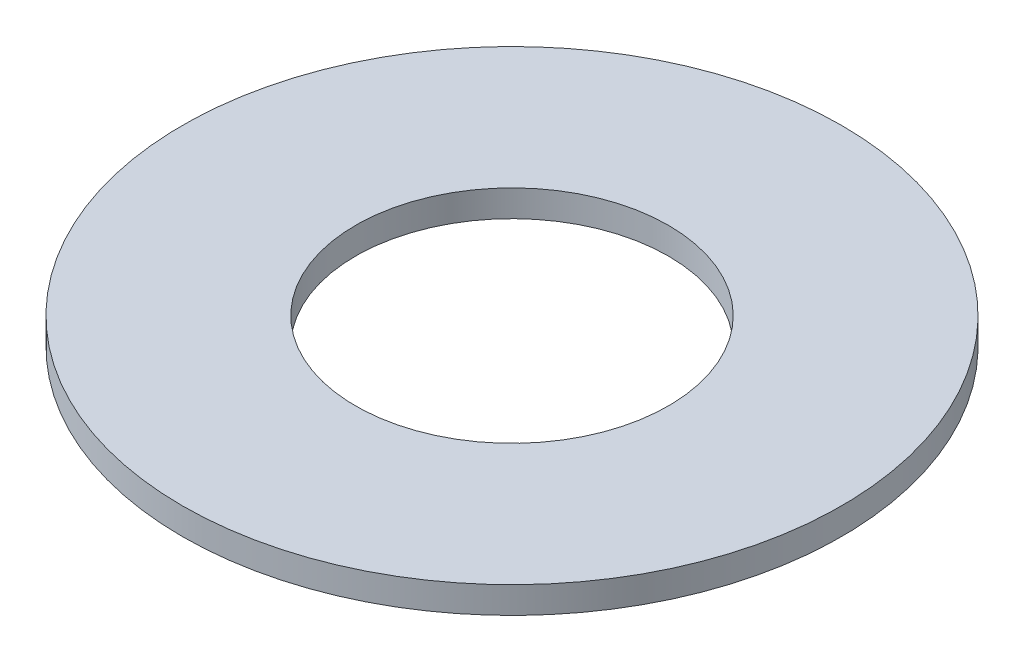
SolidWorks part; units mm, degrees
ref_plane "Front Plane" through (0, 0, 0) normal (0, 0, 1) x (1, 0, 0)
ref_plane "Top Plane" through (0, 0, 0) normal (0, 1, 0) x (1, 0, 0)
ref_plane "Right Plane" through (0, 0, 0) normal (1, 0, 0) x (0, 0, -1)
sketch "Sketch1" plane through (0, 0, 0) normal (0, 1, 0) x (1, 0, 0)
  circle A0 centre (0, 0) radius 12.36
  dimension "D1" = 24.72
extrude "Boss-Extrude1" add sketch "Sketch1" along normal blind 1
sketch "Sketch2" plane through (0, 0, 0) normal (0, -1, 0) x (-1, 0, 0)
  circle A0 centre (0, 0) radius 5.8674
  dimension "D1" = 11.7348
extrude "Cut-Extrude1" cut sketch "Sketch2" against normal through all
sketch "Sketch4" plane through (0, 1, 0) normal (0, 1, 0) x (1, 0, 0)
  circle A0 centre (0, 0) radius 12.0429 construction
  text T0 "<b>1mm</b>" font "Cambria" height 5.08
extrude "Cut-Extrude2" [suppressed] cut sketch "Sketch4" against normal blind 0.2
